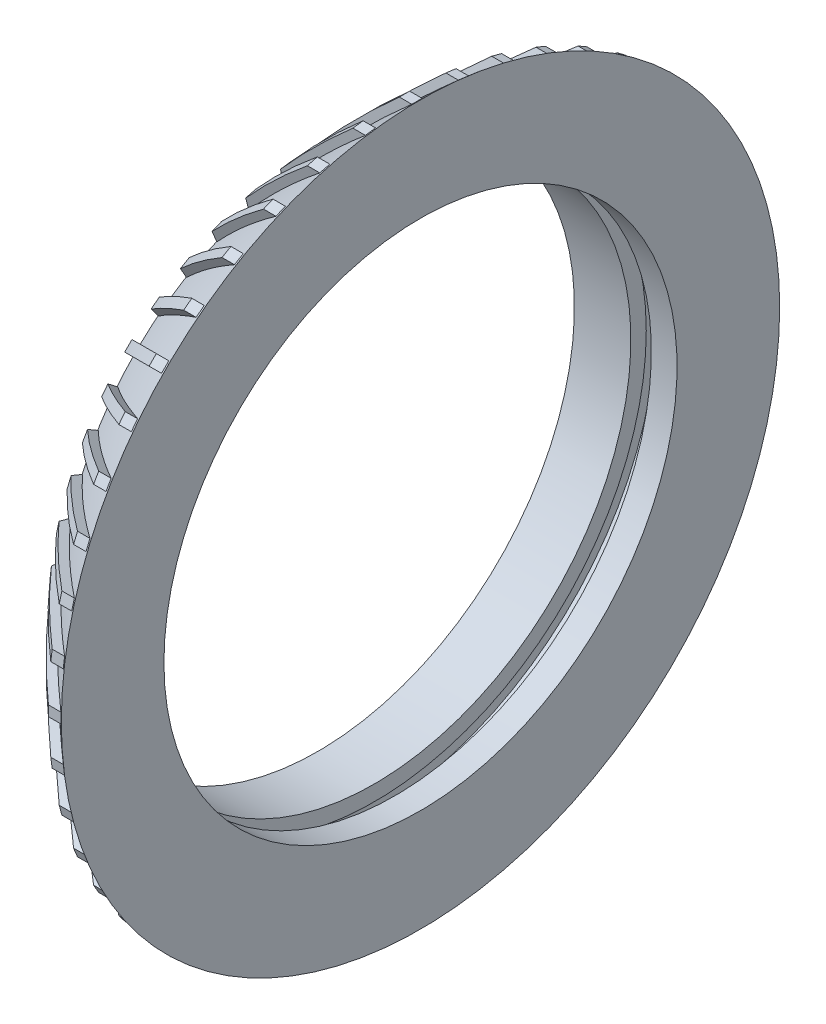
SolidWorks part; units mm, degrees
ref_plane "Front Plane" through (0, 0, 0) normal (0, 0, 1) x (1, 0, 0)
ref_plane "Top Plane" through (0, 0, 0) normal (0, 1, 0) x (1, 0, 0)
ref_plane "Right Plane" through (0, 0, 0) normal (1, 0, 0) x (0, 0, -1)
sketch "Sketch1" plane through (0, 0, 0) normal (0, 1, 0) x (1, 0, 0)
  line L0 (-32.809, 0) -> (42.2472, 0) construction
  line L1 (-10, 25) -> (-4.5, 25)
  line L2 (-5, 26.5) -> (-5, 28)
  line L3 (-5, 28) -> (-2, 28)
  line L4 (-2, 28) -> (-2, 26.5)
  line L5 (-2.5, 25) -> (0, 25)
  line L6 (0, 25) -> (0, 35)
  line L7 (-3.5, 27.1046) -> (-3.5, 23.1339) construction
  line L8 (-4.5, 25) -> (-4.5, 26.5)
  line L9 (-4.5, 26.5) -> (-5, 26.5)
  line L10 (-2.5, 26.5) -> (-2, 26.5)
  line L11 (-2.5, 26.5) -> (-2.5, 25)
  arc A3 (0, 35) -> (-10, 25) centre (65.5337, -40.5337) ccw
  dimension "D5" = 10
  dimension "D2" = 10
  dimension "D3" = 100
  dimension "D1" = 25
  dimension "D4" = 1
  dimension "D6" = 3.5
  dimension "D7" = 2
  dimension "D8" = 3
  dimension "D9" = 1.5
  dimension "D10" = 1.5
  dimension "D11" = 1.5
revolve "Revolve1" add sketch "Sketch1" angle 360 about L0
sketch "Sketch2" plane through (0, 0, 0) normal (0, 1, 0) x (1, 0, 0)
  line L3 (-9.6703, 25.1988) -> (-9.6703, 26.5857)
  line L5 (-1.5587, 34.6943) -> (-0.0467, 34.6943)
  arc A6 (-0.5243, 35.6043) -> (-10.6043, 25.5243) centre (65.5337, -40.5337) ccw
  arc A7 (-0.0467, 34.6943) -> (-9.6703, 25.1988) centre (65.0757, -40.9305) ccw
  arc A8 (-1.5587, 34.6943) -> (-9.6703, 26.5857) centre (65.5337, -40.5337) ccw
  dimension "D1" = 0.8
extrude "Boss-Extrude1" add sketch "Sketch2" along normal mid plane 1
pattern_circular "CirPattern1" count 48 over 360 about axis through (0, 0, 0) along (1, 0, 0) of "Boss-Extrude1"
